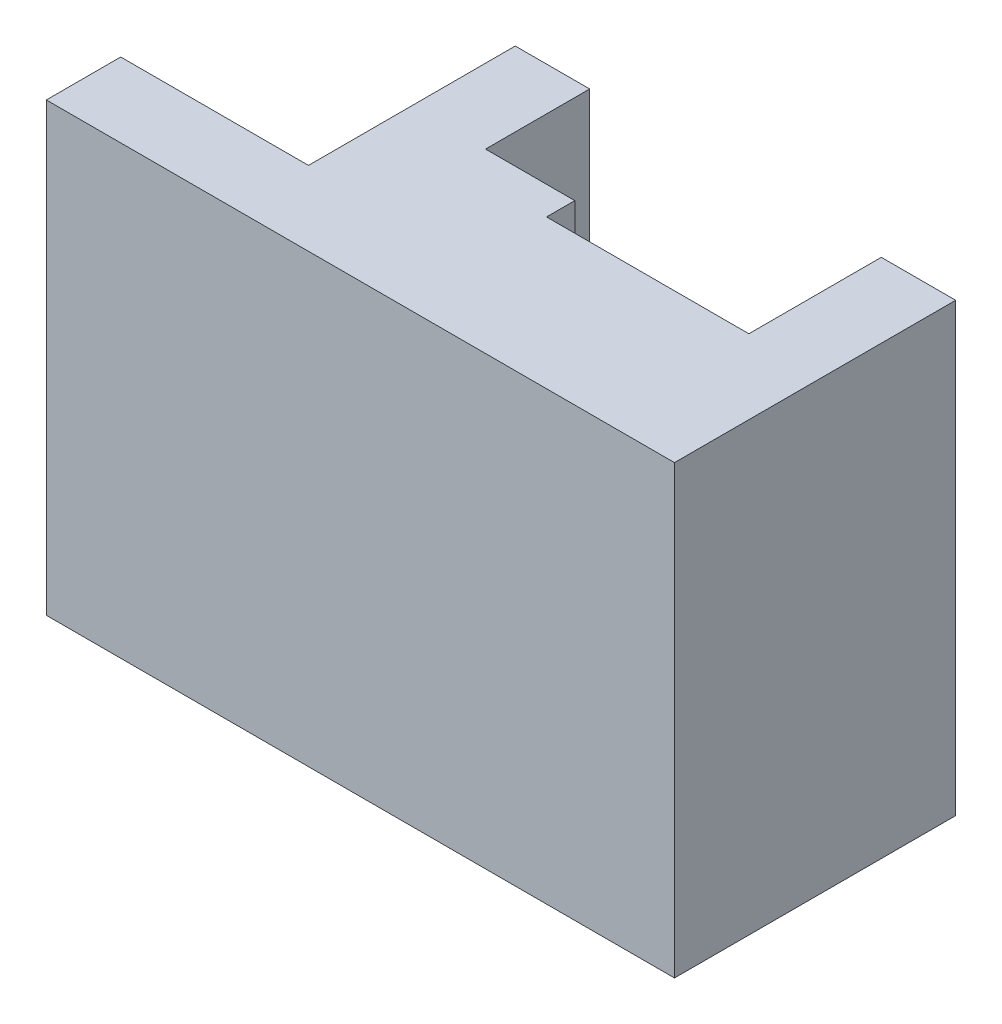
SolidWorks part; units mm, degrees
ref_plane "Front" through (0, 0, 0) normal (0, 0, 1) x (1, 0, 0)
ref_plane "Top" through (0, 0, 0) normal (0, 1, 0) x (1, 0, 0)
ref_plane "Right" through (0, 0, 0) normal (1, 0, 0) x (0, 0, -1)
sketch "Sketch1" plane through (0, 0, 0) normal (0, 1, 0) x (1, 0, 0)
  line L0 (47.2694, 24.003) -> (53.6194, 24.003)
  line L1 (53.6194, 24.003) -> (53.6194, 0)
  line L2 (53.6194, 0) -> (0, 0)
  line L3 (0, 0) -> (0, 6.35)
  line L4 (0, 6.35) -> (16.0274, 6.35)
  line L5 (16.0274, 6.35) -> (16.0274, 24.003)
  line L6 (16.0274, 24.003) -> (22.3774, 24.003)
  line L7 (22.3774, 24.003) -> (22.3774, 15.113)
  line L8 (22.3774, 15.113) -> (29.9974, 15.113)
  line L9 (29.9974, 15.113) -> (29.9974, 12.7)
  line L10 (29.9974, 12.7) -> (47.2694, 12.7)
  line L11 (47.2694, 12.7) -> (47.2694, 24.003)
  point P4 (0, 0)
  point P13 (0, 0)
  point P16 (0, 0)
  point P18 (16.0274, 5.549)
  point P19 (27.2949, 15.113)
  dimension "D1" = 7.62
  dimension "D2" = 17.272
  dimension "D3" = 16.0274
  dimension "D4" = 6.35
  dimension "D5" = 12.7
  dimension "D6" = 2.413
  dimension "D7" = 8.89
  dimension "D8" = 6.35
  dimension "D9" = 6.35
extrude "Boss-Extrude1" add sketch "Sketch1" along normal blind 38.1
